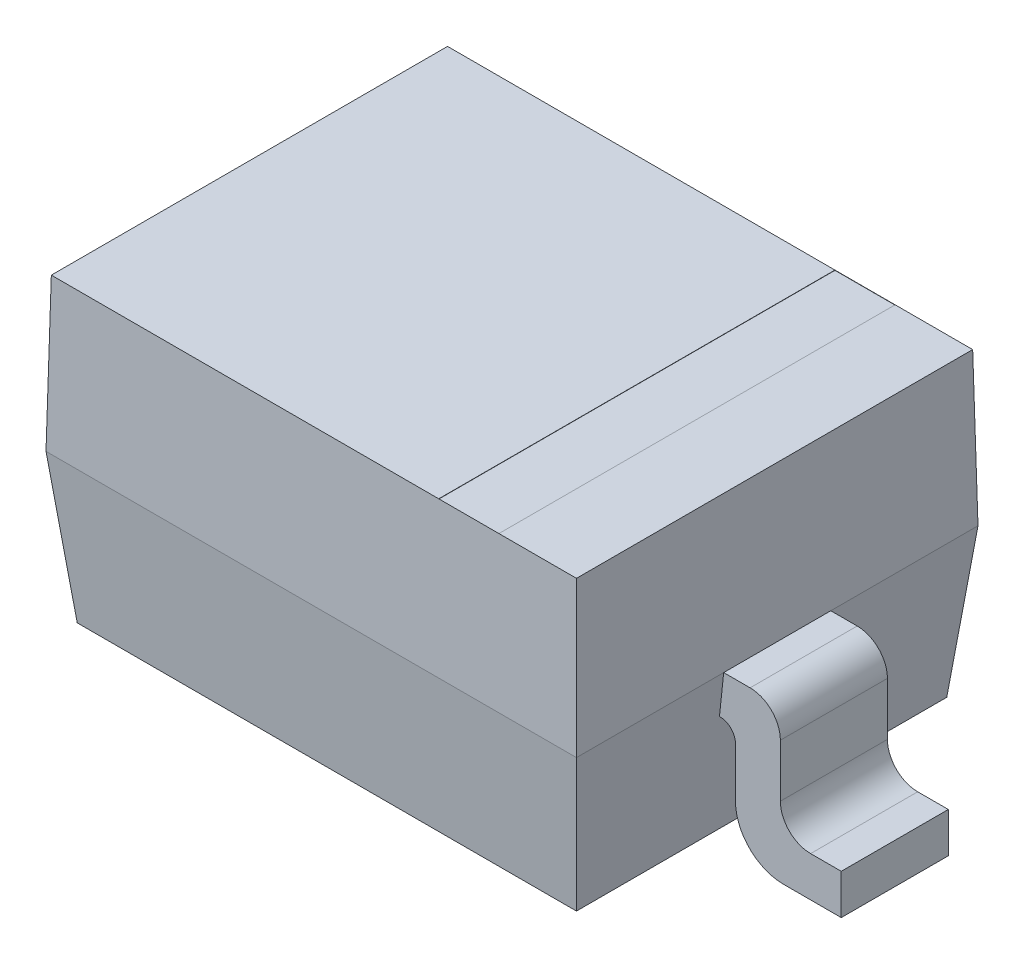
SolidWorks part; units mm, degrees
ref_plane "Alzado" through (0, 0, 0) normal (0, 0, 1) x (1, 0, 0)
ref_plane "Planta" through (0, 0, 0) normal (0, 1, 0) x (1, 0, 0)
ref_plane "Vista lateral" through (0, 0, 0) normal (1, 0, 0) x (0, 0, -1)
sketch "Croquis1" plane through (0, 0, 0) normal (0, 0, 1) x (1, 0, 0)
  line L0 (0, 0) -> (-1.95, 0)
  line L1 (-1.95, 0) -> (-1.95, -0.15) construction
  line L2 (-1.95, -0.15) -> (0, -0.15)
  line L3 (-1.95, -0.15) -> (-2.405, -0.15) construction
  line L4 (-2.405, -0.15) -> (-2.405, -0.7504) construction
  line L5 (-0.975, 0) -> (-0.975, -0.5732) construction
  line L6 (-0.975, -0.5732) -> (-2.6094, -0.5732) construction
  line L7 (-0.975, -0.5732) -> (0.589, -0.5732) construction
  line L8 (-2.6094, -0.5732) -> (-2.6094, -0.3733) construction
  line L9 (-2.405, -0.3733) -> (-2.0097, -0.3733) construction
  line L10 (-2.0097, -0.3733) -> (-2.0097, -0.5732) construction
  line L11 (-1.95, -0.15) -> (-1.9525, -0.15)
  line L12 (-2.0097, -0.2072) -> (-2.0097, -0.3938)
  line L13 (-2.1891, -0.5732) -> (-2.405, -0.5732)
  line L14 (-2.405, -0.5732) -> (-2.405, -0.4233)
  line L15 (-2.405, -0.4233) -> (-2.2905, -0.4233)
  line L16 (-2.1775, -0.3103) -> (-2.1775, -0.15)
  line L17 (-2.1775, -0.15) -> (-2.1775, -0.113)
  line L18 (-2.0645, 0) -> (-1.95, 0)
  line L19 (0, -0.15) -> (0.455, -0.15) construction
  line L20 (0, 0) -> (0, -0.15) construction
  line L21 (0.1145, 0) -> (0, 0)
  line L22 (0, -0.15) -> (0.0025, -0.15)
  line L23 (0.0597, -0.3733) -> (0.0597, -0.5732) construction
  line L24 (0.455, -0.3733) -> (0.0597, -0.3733) construction
  line L25 (0.2275, -0.15) -> (0.2275, -0.113)
  line L26 (0.2275, -0.3103) -> (0.2275, -0.15)
  line L27 (0.455, -0.4233) -> (0.3405, -0.4233)
  line L28 (0.455, -0.5732) -> (0.455, -0.4233)
  line L29 (0.2391, -0.5732) -> (0.455, -0.5732)
  line L30 (0.0597, -0.2072) -> (0.0597, -0.3938)
  arc A0 (-2.1891, -0.5732) -> (-2.0097, -0.3938) centre (-2.1891, -0.3938) ccw
  arc A1 (-2.1775, -0.3103) -> (-2.2905, -0.4233) centre (-2.2905, -0.3103) cw
  arc A2 (-2.1775, -0.113) -> (-2.0645, 0) centre (-2.0645, -0.113) cw
  arc A3 (-2.0097, -0.2072) -> (-1.9525, -0.15) centre (-1.9525, -0.2072) cw
  arc A4 (0.0597, -0.2072) -> (0.0025, -0.15) centre (0.0025, -0.2072) ccw
  arc A5 (0.2275, -0.113) -> (0.1145, 0) centre (0.1145, -0.113) ccw
  arc A6 (0.2275, -0.3103) -> (0.3405, -0.4233) centre (0.3405, -0.3103) ccw
  arc A7 (0.2391, -0.5732) -> (0.0597, -0.3938) centre (0.2391, -0.3938) cw
  point P22 (0, 0)
  point P31 (-2.0097, -0.15)
  point P51 (0.0597, -0.15)
  dimension "D3" = 0.1794
  dimension "D4" = 0.113
  dimension "D5" = 0.113
  dimension "D6" = 0.0572
  dimension "D1" = 1.95
  dimension "D2" = 0.15
extrude "Saliente-Extruir1" add sketch "Croquis1" along normal blind 0.4
sketch "Croquis2" plane through (0, 0, 0) normal (0, 1, 0) x (1, 0, 0)
  line L0 (-0.975, -0.4) -> (-0.975, 0) construction
  line L1 (0.1145, -0.4) -> (-2.0645, -0.4) construction
  line L2 (0.1145, 0) -> (-2.0645, 0) construction
  line L3 (-2.0645, -0.2) -> (0.1145, -0.2) construction
  line L4 (-2.0645, -0.4) -> (-2.0645, 0) construction
  line L5 (0.1145, -0.4) -> (0.1145, 0) construction
  line L7 (0.0158, -0.95) -> (-1.9658, -0.95)
  line L8 (0.0158, -0.95) -> (0.0158, 0.55)
  line L9 (0.0158, 0.55) -> (-1.9658, 0.55)
  line L10 (-1.9658, -0.95) -> (-1.9658, 0.55)
  line L11 (0.0158, -0.95) -> (-1.9658, 0.55) construction
  line L12 (0.0158, 0.55) -> (-1.9658, -0.95) construction
  line L13 (0.0025, -0.4) -> (0.0025, 0) construction
  line L14 (-0.975, 0) -> (-0.975, 0.234) construction
  line L15 (-1.9658, -0.4) -> (-1.9658, 0) construction
  line L16 (-0.975, 0) -> (0.0025, 0) construction
  line L17 (0.0025, 0) -> (0.0025, -0.4) construction
  line L18 (0.0025, -0.4) -> (-1.9658, -0.4) construction
  point P12 (-0.975, -0.2)
  dimension "D1" = 1.5
extrude "Saliente-Extruir2" add sketch "Croquis2" along normal blind 0.57 draft 1 and the other way blind 0.555 draft 6
sketch "Croquis3" plane through (0, 0.57, 0) normal (0, 1, 0) x (1, 0, 0)
  line L0 (-0.5086, 0.5401) -> (-0.5086, -0.9401)
  line L1 (0.0059, 0.5401) -> (-1.9559, 0.5401) construction
  line L2 (-1.9559, -0.9401) -> (0.0059, -0.9401) construction
  line L3 (-0.5086, -0.9401) -> (-0.2838, -0.9401)
  line L4 (-0.2838, -0.9401) -> (-0.2838, 0.5401)
  line L5 (-0.2838, 0.5401) -> (-0.5086, 0.5401)
extrude "Cortar-Extruir1" cut sketch "Croquis3" against normal blind 0.001
